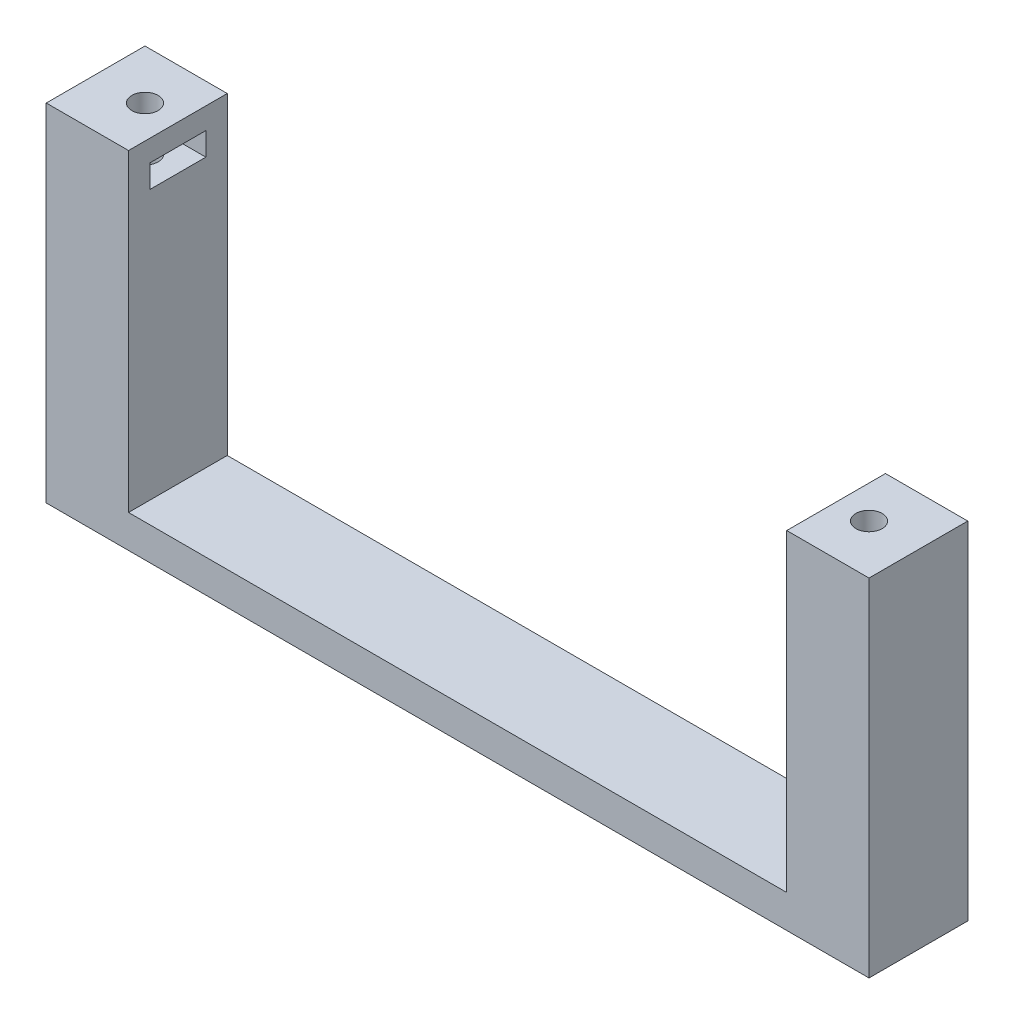
SolidWorks part; units mm, degrees
ref_plane "Front Plane" through (0, 0, 0) normal (0, 0, 1) x (1, 0, 0)
ref_plane "Top Plane" through (0, 0, 0) normal (0, 1, 0) x (1, 0, 0)
ref_plane "Right Plane" through (0, 0, 0) normal (1, 0, 0) x (0, 0, -1)
sketch "Sketch2" plane through (0, 0, 0) normal (0, 1, 0) x (1, 0, 0)
  line L0 (44, 0) -> (-44, 0)
  line L1 (-50, 6) -> (50, 6)
  line L2 (-50, 6) -> (-50, -6)
  line L3 (-50, -6) -> (50, -6)
  line L4 (50, 6) -> (50, -6)
  line L5 (-50, 6) -> (50, -6) construction
  line L6 (-50, -6) -> (50, 6) construction
  circle A0 centre (-44, 0) radius 1.6
  circle A1 centre (44, 0) radius 1.6
  point P0 (0, 0)
  point P9 (0, 0)
  dimension "D4" = 3.2
  dimension "D5" = 3.2
  dimension "D1" = 100
  dimension "D2" = 12
  dimension "D3" = 88
extrude "body" add sketch "Sketch2" along normal blind 4 contours L2 L1 L4 L3 | A0 | A1
sketch "Sketch4" plane through (0, 4, 0) normal (0, 1, 0) x (1, 0, 0)
  line L0 (-50, -6) -> (50, -6) construction
  line L1 (-50, 6) -> (-40, 6)
  line L2 (-50, 6) -> (-50, -6)
  line L3 (-50, -6) -> (-40, -6)
  line L4 (-40, 6) -> (-40, -6)
  line L6 (50, 6) -> (40, 6)
  line L7 (50, 6) -> (50, -6)
  line L8 (50, -6) -> (40, -6)
  line L9 (40, 6) -> (40, -6)
  circle A0 centre (-44, 0) radius 1.6
  circle A1 centre (44, 0) radius 1.6
  dimension "D1" = 10
  dimension "D2" = 10
extrude "wings" add sketch "Sketch4" along normal blind 38.1
sketch "Sketch6" plane through (40, 0, 0) normal (-1, 0, 0) x (0, 0, 1)
  line L0 (0, 42.1) -> (0, 38.1)
  line L1 (-6, 42.1) -> (6, 42.1) construction
  line L3 (-3.4, 39.5) -> (3.4, 39.5)
  line L4 (-3.4, 39.5) -> (-3.4, 36.7)
  line L5 (-3.4, 36.7) -> (3.4, 36.7)
  line L6 (3.4, 39.5) -> (3.4, 36.7)
  line L7 (-3.4, 39.5) -> (3.4, 36.7) construction
  line L8 (-3.4, 36.7) -> (3.4, 39.5) construction
  dimension "D1" = 4
  dimension "D2" = 6.8
  dimension "D3" = 2.8
extrude "captive-nut" cut sketch "Sketch6" against normal blind 8.5
pattern_circular "CirPattern1" count 2 over 360 about axis through (0, 0, 0) along (0, 1, 0) of "captive-nut"
